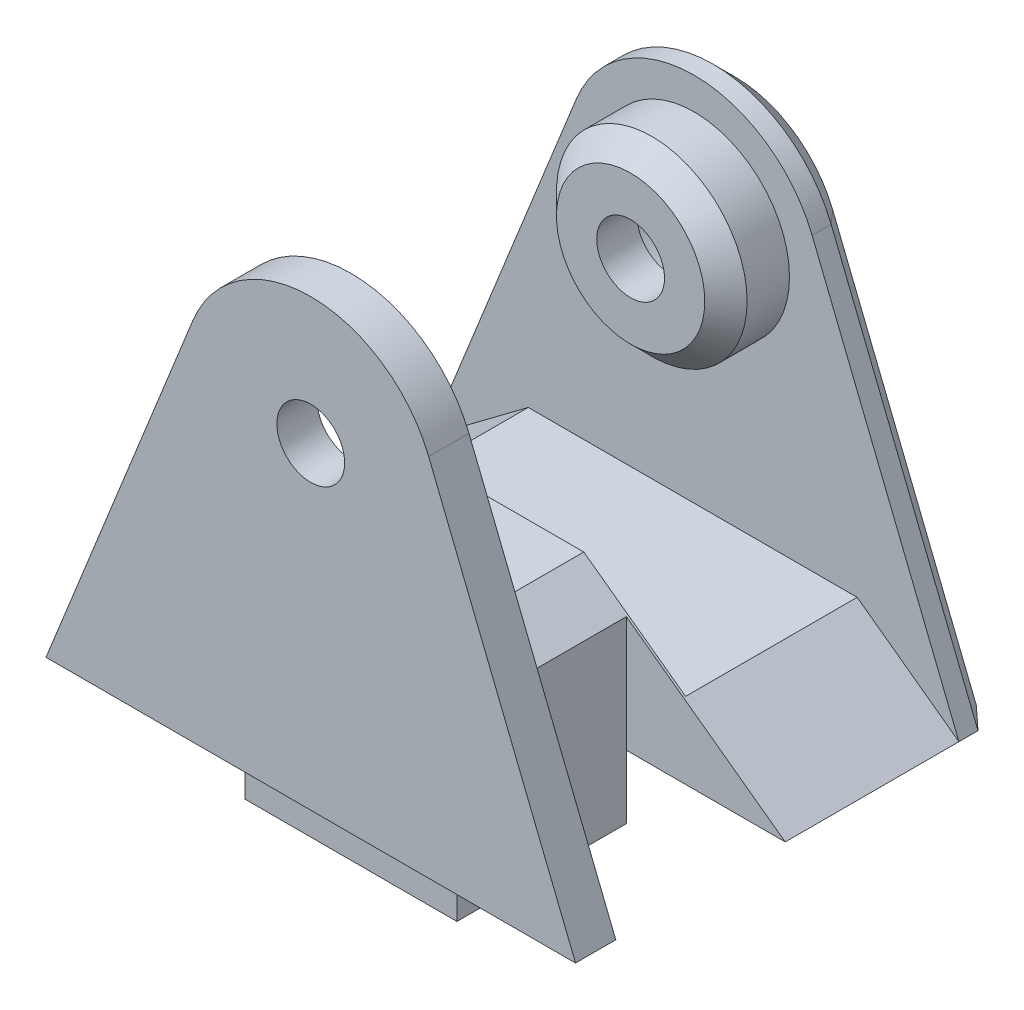
SolidWorks part; units mm, degrees
ref_plane "Alzado" through (0, 0, 0) normal (0, 0, 1) x (1, 0, 0)
ref_plane "Planta" through (0, 0, 0) normal (0, 1, 0) x (1, 0, 0)
ref_plane "Vista lateral" through (0, 0, 0) normal (1, 0, 0) x (0, 0, -1)
sketch "Croquis1" plane through (0, 0, 0) normal (0, 0, 1) x (1, 0, 0)
  line L0 (-12.5, -15) -> (-5.5666, 2.2389)
  line L1 (5.5666, 2.2389) -> (12.5, -15)
  line L2 (12.5, -15) -> (-12.5, -15)
  line L3 (0, 0) -> (0, -50000) construction
  circle A0 centre (0, 0) radius 1.6
  arc A1 (-5.5666, 2.2389) -> (5.5666, 2.2389) centre (0, 0) cw
  point P7 (0, -15)
  dimension "D1" = 3.2
  dimension "D2" = 6
  dimension "D3" = 15
  dimension "D4" = 25
extrude "Saliente-Extruir1" add sketch "Croquis1" along normal mid plane 20
sketch "Croquis2" plane through (0, 0, 0) normal (0, 0, 1) x (1, 0, 0)
  line L0 (12.5, -15) -> (5.5666, 2.2389) construction
  line L1 (-12.5, -15) -> (-7.5, 0)
  line L2 (12.5, -15) -> (7.5, 0)
  line L5 (-5.5666, 2.2389) -> (-12.5, -15) construction
  line L6 (-12.5, -15) -> (12.5, -15) construction
  line L7 (-12.5, -15) -> (-3.1648, -8)
  line L8 (-3.1648, -8) -> (2.8886, -8)
  line L9 (2.8886, -8) -> (12.5, -15)
  arc A0 (7.5, 0) -> (-7.5, 0) centre (0, 0) ccw
  dimension "D1" = 15
  dimension "D2" = 8
extrude "Cortar-Extruir1" cut sketch "Croquis2" against normal blind 8.1 and the other way blind 8.1
sketch "Croquis3" plane through (0, 0, 0) normal (0, 0, 1) x (1, 0, 0)
  line L0 (0, 0) -> (0, -50000) construction
  line L1 (-12.5, -15) -> (12.5, -15) construction
  line L2 (-5, 10.7975) -> (5, 10.7975)
  line L3 (-5, 10.7975) -> (-5, -15)
  line L4 (-5, -15) -> (5, -15)
  line L5 (5, 10.7975) -> (5, -15)
  line L6 (-5, 10.7975) -> (5, -15) construction
  line L7 (-5, -15) -> (5, 10.7975) construction
  point P3 (0, -2.1012)
  dimension "D1" = 10
extrude "Cortar-Extruir2" cut sketch "Croquis3" against normal blind 8 from surface at 8.1 flip side to cut starting at face at (1.6, 0, 8.1)
sketch "Croquis4" plane through (0, -15, 0) normal (0, -1, 0) x (1, 0, 0)
  line L1 (-5, 0.1) -> (5, 0.1)
  line L2 (-5, 0.1) -> (-5, 8.1)
  line L3 (-5, 8.1) -> (5, 8.1)
  line L4 (5, 0.1) -> (5, 8.1)
  line L5 (-5, 0.1) -> (5, 8.1) construction
  line L6 (-5, 8.1) -> (5, 0.1) construction
  point P0 (0, 0)
  point P5 (0, 0)
  point P6 (0, 0)
  point P8 (5, 9)
  point P11 (5, -2.714)
  point P12 (5, 1)
  point P14 (-5, 1)
extrude "Saliente-Extruir3" add sketch "Croquis4" along normal blind 3
sketch "Croquis5" plane through (0, 0, 0) normal (1, 0, 0) x (0, 0, -1)
  line L0 (-8.1, -8) -> (8.1, -8) construction
  line L1 (0, -8) -> (8.1, -8)
  line L2 (0, -8) -> (0, -11.5)
  line L3 (0, -11.5) -> (8.1, -11.5)
  line L4 (8.1, -8) -> (8.1, -11.5)
  line L5 (0, -8) -> (8.1, -11.5) construction
  line L6 (0, -11.5) -> (8.1, -8) construction
  line L7 (8.1, -8) -> (8.1, -15) construction
  point P4 (4.05, -9.75)
extrude "Cortar-Extruir3" cut sketch "Croquis5" against normal through all both and the other way through all
sketch "Croquis6" plane through (0, 0, -8.1) normal (0, 0, 1) x (1, 0, 0)
  circle A0 centre (0, 0) radius 4.5
  circle A1 centre (0, 0) radius 1.6
  dimension "D1" = 9
extrude "Saliente-Extruir4" add sketch "Croquis6" along normal blind 3
chamfer "Chaflán1" distance 1 angle 45 1 edges at (4.5, 0, -5.1)
sketch "Croquis7" plane through (0, 0, -10) normal (0, 0, -1) x (-1, 0, 0)
  circle A0 centre (0, 0) radius 3.5
  dimension "D1" = 7
extrude "Cortar-Extruir4" cut sketch "Croquis7" against normal blind 3
chamfer "Chaflán2" distance 1 angle 45 3 edges at (9.0333, -6.3806, -10) (-9.0333, -6.3806, -10) (0, 6, -10)
